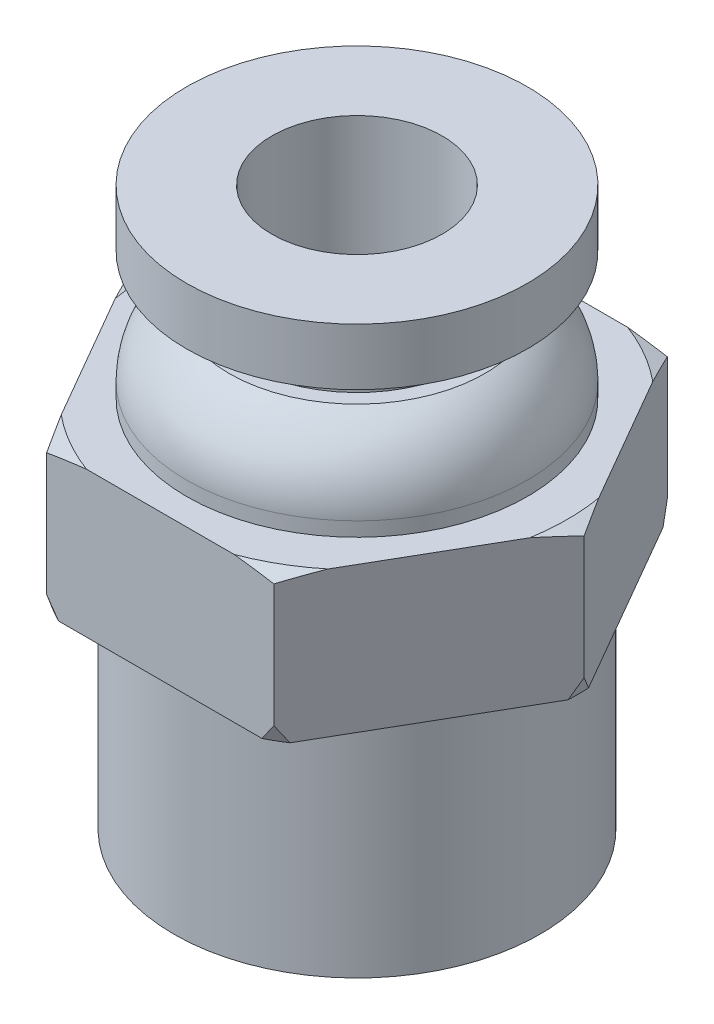
SolidWorks part; units mm, degrees
ref_plane "前视基准面" through (0, 0, 0) normal (0, 0, 1) x (1, 0, 0)
ref_plane "上视基准面" through (0, 0, 0) normal (0, 1, 0) x (1, 0, 0)
ref_plane "右视基准面" through (0, 0, 0) normal (1, 0, 0) x (0, 0, -1)
sketch "草图1" plane through (0, 0, 0) normal (0, 0, 1) x (1, 0, 0)
  line L0 (0, 26.7594) -> (0, -26.7594) construction
  line L1 (3, 19.6222) -> (6, 19.6222)
  line L2 (6, 19.6222) -> (6, 17.6222)
  line L3 (6, 17.6222) -> (3.5, 17.6222)
  line L4 (3.5, 17.6222) -> (3.5, 16.6222)
  line L5 (3.5, 16.6222) -> (4, 16.6222)
  line L6 (4, 16.6222) -> (4, 16.1222)
  line L7 (4, 16.1222) -> (4.5, 16.1222)
  line L8 (3, 19.6222) -> (3, 6.6222)
  line L9 (6, 13.6222) -> (6, 13.1222)
  line L10 (6, 13.1222) -> (8, 13.1222)
  line L11 (8, 13.1222) -> (8, 8)
  line L12 (8, 8) -> (6.45, 8)
  line L13 (6.45, 8) -> (6.45, 0)
  line L14 (6.45, 0) -> (0, 0)
  line L15 (0, 0) -> (0, 6.6222)
  line L16 (3, 6.6222) -> (0, 6.6222)
  line L17 (0, 6.6222) -> (0, 0)
  line L18 (0, 0) -> (-0.0662, -0.1188)
  line L19 (0, 3) -> (5.45, 3)
  line L20 (5.45, 3) -> (5.45, 0)
  arc A0 (4.5, 16.1222) -> (6, 13.6222) centre (3.1667, 13.6222) cw
  point P4 (0, 0)
  dimension "D1" = 12
  dimension "D2" = 2
  dimension "D3" = 12
  dimension "D4" = 0.5
  dimension "D5" = 0.5
  dimension "1." = 2
  dimension "D7" = 1
  dimension "D8" = 0.5
  dimension "D9" = 4.5
  dimension "D10" = 16
  dimension "D11" = 0.5
  dimension "D12" = 5.1222
  dimension "D13" = 8
  dimension "D14" = 12.9
  dimension "D15" = 6
  dimension "D17" = 3
  dimension "D18" = 1
  dimension "D19" = 13
revolve "旋转1" add sketch "草图1" angle 360 about L0
chamfer "倒角1" distance 0.2 distance2 0.6 2 edges at (0, 8, 8) (0, 13.1222, 8)
sketch "草图2" plane through (0, 0, 0) normal (0, 1, 0) x (1, 0, 0)
  line L1 (2, 1.1547) -> (0, 2.3094)
  line L2 (0, 2.3094) -> (-2, 1.1547)
  line L3 (-2, 1.1547) -> (-2, -1.1547)
  line L4 (-2, -1.1547) -> (0, -2.3094)
  line L5 (0, -2.3094) -> (2, -1.1547)
  line L6 (2, -1.1547) -> (2, 1.1547)
  circle A0 centre (0, 0) radius 2 construction
  dimension "D1" = 4
extrude "切除-拉伸1" cut sketch "草图2" along normal up to surface (6.6222 mm away) up to face at (0, 6.6222, 3)
sketch "草图3" plane through (0, 0, 0) normal (0, 1, 0) x (1, 0, 0)
  line L1 (8, 0) -> (4, 6.9282)
  line L2 (4, 6.9282) -> (-4, 6.9282)
  line L3 (-4, 6.9282) -> (-8, 0)
  line L4 (-8, 0) -> (-4, -6.9282)
  line L5 (-4, -6.9282) -> (4, -6.9282)
  line L6 (4, -6.9282) -> (8, 0)
  circle A0 centre (0, 0) radius 6.9282 construction
  circle A1 centre (0, 0) radius 8 construction
  circle A2 centre (0, 0) radius 13
  dimension "D1" = 5
extrude "切除-拉伸3" cut sketch "草图3" along normal through all
